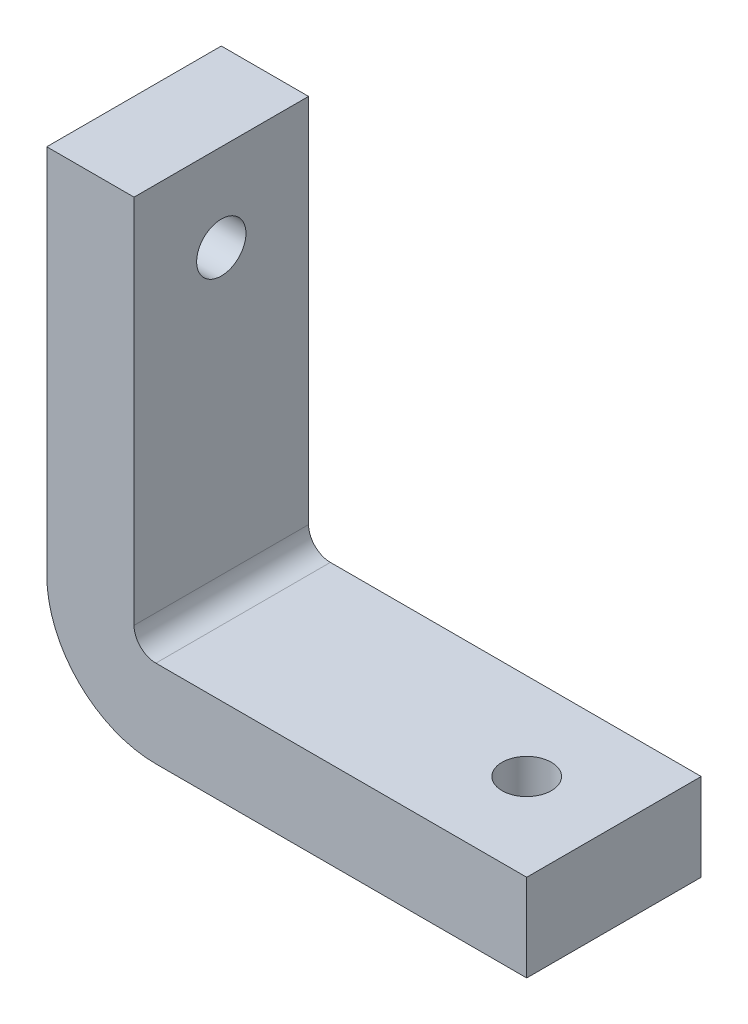
SolidWorks part; units mm, degrees
ref_plane "Front Plane" through (0, 0, 0) normal (0, 0, 1) x (1, 0, 0)
ref_plane "Top Plane" through (0, 0, 0) normal (0, 1, 0) x (1, 0, 0)
ref_plane "Right Plane" through (0, 0, 0) normal (1, 0, 0) x (0, 0, -1)
sketch "Sketch3" plane through (0, 0, 0) normal (0, 0, 1) x (1, 0, 0)
  line L0 (1, 0) -> (18, 0)
  line L1 (0, 1) -> (0, 18)
  line L2 (-4, 1) -> (-4, 18)
  line L3 (1, -4) -> (18, -4)
  line L4 (0, 18) -> (-4, 18)
  line L5 (18, 0) -> (18, -4)
  arc A0 (1, 0) -> (0, 1) centre (1, 1) cw
  arc A1 (1, -4) -> (-4, 1) centre (1, 1) cw
  point P7 (0, 0)
  dimension "D1" = 1
  dimension "D3" = 22
  dimension "D4" = 22
  dimension "D2" = 4
extrude "Boss-Extrude1" add sketch "Sketch3" along normal mid plane 8
hole_wizard "#4-40 Tapped Hole1" positions "Sketch4" profile "Sketch5" tap size "#4-40" standard "ANSI Inch"
sketch "Sketch4" plane through (0, 0, 0) normal (1, 0, 0) x (0, 0, -1)
  line L1 (-4, 18) -> (4, 18) construction
  point P0 (0, 14)
  dimension "D1" = 4
sketch "Sketch5" plane through (0, 14, 0) normal (0, 1, 0) x (0, 0, -1)
  line L0 (0, 0) -> (0, 8.2792)
  line L1 (0, 8.2792) -> (1.1303, 7.6)
  line L2 (1.1303, 7.6) -> (1.1303, 0)
  line L5 (1.1303, 0) -> (0, 0)
  line L10 (0, 8.2792) -> (-1.1303, 7.6) construction
  line L11 (0, -6.35) -> (0, 107.95) construction
  dimension "Tap Drill Dia." = 2.2606
  dimension "Tap Drill Depth" = 7.6
  dimension "Drill Angle" = 118
cosmetic thread "Hole Thread1" parameters "D1"=5.69, "D2"=2.8448
hole_wizard "#4-40 Tapped Hole2" positions "Sketch6" profile "Sketch7" tap size "#4-40" standard "ANSI Inch"
sketch "Sketch6" plane through (0, 0, 0) normal (0, 1, 0) x (1, 0, 0)
  line L1 (18, -4) -> (18, 4) construction
  point P0 (14, 0)
  dimension "D1" = 4
sketch "Sketch7" plane through (14, 0, 0) normal (1, 0, 0) x (0, 0, 1)
  line L0 (0, 0) -> (0, 8.2792)
  line L1 (0, 8.2792) -> (1.1303, 7.6)
  line L2 (1.1303, 7.6) -> (1.1303, 0)
  line L5 (1.1303, 0) -> (0, 0)
  line L10 (0, 8.2792) -> (-1.1303, 7.6) construction
  line L11 (0, -6.35) -> (0, 107.95) construction
  dimension "Tap Drill Dia." = 2.2606
  dimension "Tap Drill Depth" = 7.6
  dimension "Drill Angle" = 118
cosmetic thread "Hole Thread2" parameters "D1"=5.69, "D2"=2.8448
